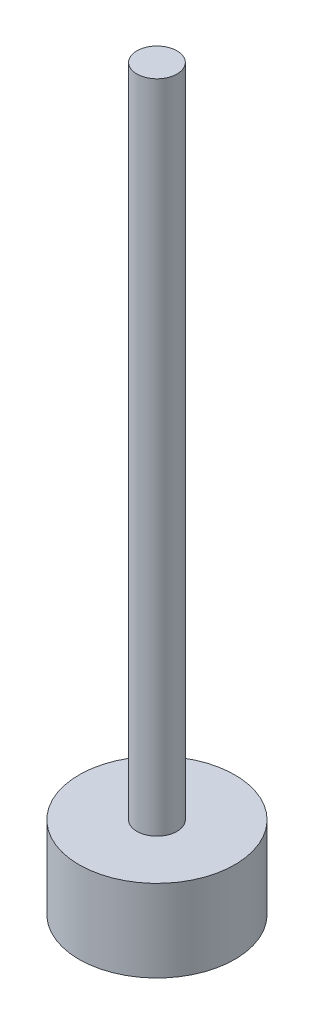
SolidWorks part; units mm, degrees
ref_plane "Front Plane" through (0, 0, 0) normal (0, 0, 1) x (1, 0, 0)
ref_plane "Top Plane" through (0, 0, 0) normal (0, 1, 0) x (1, 0, 0)
ref_plane "Right Plane" through (0, 0, 0) normal (1, 0, 0) x (0, 0, -1)
sketch "Sketch1" plane through (0, 0, 0) normal (0, 1, 0) x (1, 0, 0)
  circle A0 centre (0, 0) radius 12.065
  dimension "D1" = 24.13
extrude "Boss-Extrude1" add sketch "Sketch1" along normal blind 12.7
sketch "Sketch2" plane through (0, 12.7, 0) normal (0, 1, 0) x (1, 0, 0)
  circle A0 centre (0, 0) radius 3.1115
  dimension "D1" = 6.223
extrude "Boss-Extrude2" add sketch "Sketch2" along normal blind 101.6
